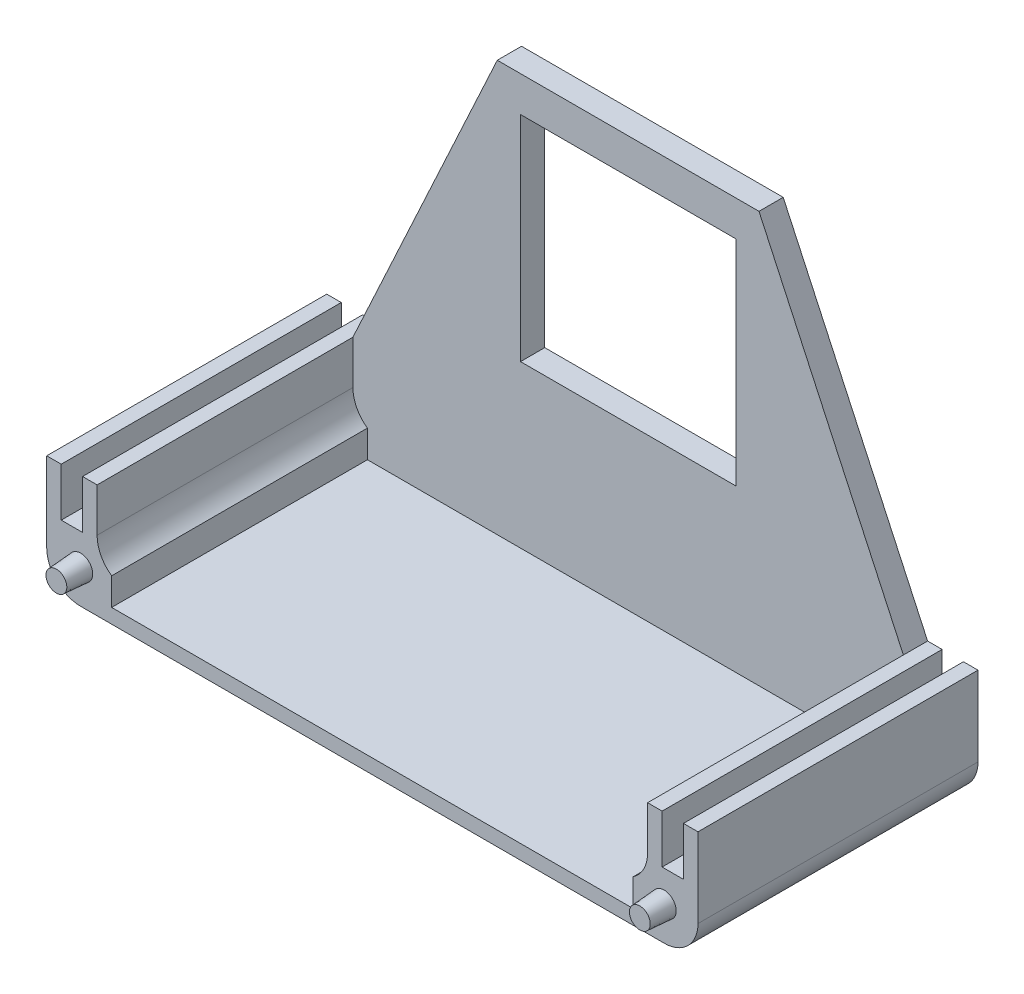
SolidWorks part; units mm, degrees
ref_plane "Спереди" through (0, 0, 0) normal (0, 0, 1) x (1, 0, 0)
ref_plane "Сверху" through (0, 0, 0) normal (0, 1, 0) x (1, 0, 0)
ref_plane "Справа" through (0, 0, 0) normal (1, 0, 0) x (0, 0, -1)
sketch "Sketch1" plane through (0, 0, 0) normal (0, 0, 1) x (1, 0, 0)
  line L21 (-42.2, 12.3095) -> (42.2, 12.3095) construction
  line L33 (-67.2, 104.5095) -> (-67.2, 19.3095) construction
  line L38 (67.2, 19.3095) -> (67.2, 104.5095) construction
  line L40 (56.8, 26.7095) -> (56.8, 97.1095) construction
  line L42 (53.8, 15.3095) -> (53.8, 20.965) construction
  line L43 (-56.8, 97.1095) -> (-56.8, 26.7095) construction
  line L44 (-53.8, 20.965) -> (-53.8, 15.3095) construction
  line L45 (-53.8, 15.3095) -> (53.8, 15.3095) construction
  line L46 (-60.2, 12.3095) -> (60.2, 12.3095)
  line L47 (-67.2, 35.7095) -> (-67.2, 19.3095)
  line L48 (67.2, 19.3095) -> (67.2, 35.7095)
  line L49 (56.8, 26.7095) -> (56.8, 35.7095)
  line L50 (53.8, 15.3095) -> (53.8, 20.965)
  line L51 (-56.8, 35.7095) -> (-56.8, 26.7095)
  line L52 (-53.8, 20.965) -> (-53.8, 15.3095)
  line L53 (-53.8, 15.3095) -> (53.8, 15.3095)
  line L54 (-59.8, 100.1095) -> (-59.8, 25.7095) construction
  line L55 (-59.8, 25.7095) -> (-64.2, 25.7095) construction
  line L56 (-64.2, 25.7095) -> (-64.2, 104.5095) construction
  line L57 (64.2, 104.5095) -> (64.2, 25.7095) construction
  line L58 (59.8, 25.7095) -> (59.8, 100.1095) construction
  line L59 (64.2, 25.7095) -> (59.8, 25.7095) construction
  line L60 (-59.8, 35.7095) -> (-59.8, 25.7095)
  line L61 (-59.8, 25.7095) -> (-64.2, 25.7095)
  line L62 (-64.2, 25.7095) -> (-64.2, 35.7095)
  line L63 (64.2, 35.7095) -> (64.2, 25.7095)
  line L64 (59.8, 25.7095) -> (59.8, 35.7095)
  line L65 (64.2, 25.7095) -> (59.8, 25.7095)
  line L66 (-56.8, 35.7095) -> (56.8, 35.7095) construction
  line L69 (-67.2, 35.7095) -> (-64.2, 35.7095)
  line L70 (-59.8, 35.7095) -> (-56.8, 35.7095)
  line L71 (56.8, 35.7095) -> (59.8, 35.7095)
  line L72 (64.2, 35.7095) -> (67.2, 35.7095)
  arc A8 (-67.2, 19.3095) -> (-60.2, 12.3095) centre (-60.2, 19.3095) ccw construction
  arc A9 (60.2, 12.3095) -> (67.2, 19.3095) centre (60.2, 19.3095) ccw construction
  arc A10 (53.8, 20.965) -> (56.8, 26.7095) centre (49.8, 26.7095) ccw construction
  arc A11 (-56.8, 26.7095) -> (-53.8, 20.965) centre (-49.8, 26.7095) ccw construction
  arc A12 (-67.2, 19.3095) -> (-60.2, 12.3095) centre (-60.2, 19.3095) ccw
  arc A13 (60.2, 12.3095) -> (67.2, 19.3095) centre (60.2, 19.3095) ccw
  arc A14 (53.8, 20.965) -> (56.8, 26.7095) centre (49.8, 26.7095) ccw
  arc A15 (-56.8, 26.7095) -> (-53.8, 20.965) centre (-49.8, 26.7095) ccw
  dimension "D1" = 10
extrude "Extrude2" add sketch "Sketch1" along normal up to vertex (57.786 mm away)
sketch "Sketch2" plane through (0, 0, 57.786) normal (0, 0, 1) x (1, 0, 0)
  circle A0 centre (-60.2, 19.3095) radius 2.5
  circle A1 centre (60.2, 19.3095) radius 2.5
  point P0 (-60.2, 19.3095)
  point P1 (60.2, 19.3095)
  dimension "D1" = 5
extrude "Extrude3" add sketch "Sketch2" along normal blind 5 draft 4
sketch "Sketch4" plane through (0, 0, 0) normal (0, 0, -1) x (-1, 0, 0)
  circle A0 centre (-60.2, 19.3095) radius 2.6
  circle A1 centre (60.2, 19.3095) radius 2.6
  dimension "D1" = 5.2
extrude "Cut-Extrude1" cut sketch "Sketch4" against normal blind 5.2 draft 3.8
sketch "Sketch3" plane through (0, 0, 0) normal (0, 0, -1) x (-1, 0, 0)
  line L0 (-27, 100.1095) -> (27, 100.1095)
  line L5 (-27, 100.1095) -> (-56.8, 35.7095)
  line L6 (27, 100.1095) -> (56.8, 35.7095)
  line L7 (-56.8, 35.7095) -> (-56.8, 26.7095) construction
  line L8 (-53.8, 20.965) -> (-53.8, 15.3095) construction
  line L11 (-53.8, 15.3095) -> (53.8, 15.3095) construction
  line L29 (53.8, 15.3095) -> (53.8, 20.965) construction
  line L30 (56.8, 26.7095) -> (56.8, 35.7095) construction
  line L31 (-56.8, 35.7095) -> (-56.8, 26.7095)
  line L32 (-53.8, 20.965) -> (-53.8, 15.3095)
  line L33 (-53.8, 15.3095) -> (53.8, 15.3095)
  line L34 (53.8, 15.3095) -> (53.8, 20.965)
  line L35 (56.8, 26.7095) -> (56.8, 35.7095)
  line L36 (-59.8, 100.1095) -> (59.8, 100.1095) construction
  line L37 (22.2091, 48.6403) -> (22.2091, 92.8045) construction
  line L38 (-22.2091, 92.8045) -> (22.2091, 92.8045) construction
  line L39 (-22.2091, 48.6403) -> (-22.2091, 92.8045) construction
  line L40 (-22.2091, 48.6403) -> (22.2091, 48.6403) construction
  line L41 (22.2091, 48.6403) -> (22.2091, 92.8045)
  line L42 (-22.2091, 92.8045) -> (22.2091, 92.8045)
  line L43 (-22.2091, 48.6403) -> (-22.2091, 92.8045)
  line L44 (-22.2091, 48.6403) -> (22.2091, 48.6403)
  arc A4 (-56.8, 26.7095) -> (-53.8, 20.965) centre (-49.8, 26.7095) ccw construction
  arc A5 (53.8, 20.965) -> (56.8, 26.7095) centre (49.8, 26.7095) ccw construction
  arc A6 (-56.8, 26.7095) -> (-53.8, 20.965) centre (-49.8, 26.7095) ccw
  arc A7 (53.8, 20.965) -> (56.8, 26.7095) centre (49.8, 26.7095) ccw
  point P6 (0, 100.1095)
  dimension "D1" = 54
extrude "Extrude4" add sketch "Sketch3" against normal blind 5 separate body
sketch "Sketch5" [suppressed] plane through (-60, 0, 0) normal (0, 0, 1) x (1, 0, 0)
  line L3 (107.5, 70.3095) -> (107.5, 30.3095) construction
  line L4 (112.5, 70.3095) -> (112.5, 30.3095)
  line L5 (102.5, 70.3095) -> (102.5, 30.3095)
  line L6 (12.5, 70.3095) -> (12.5, 30.3095) construction
  line L7 (17.5, 70.3095) -> (17.5, 30.3095)
  line L8 (7.5, 70.3095) -> (7.5, 30.3095)
  line L9 (107.5, 50.3095) -> (12.5, 50.3095) construction
  line L22 (113.8, 15.3095) -> (6.2, 15.3095) construction
  line L24 (119.8, 35.7095) -> (119.8, 100.1095)
  line L25 (119.8, 100.1095) -> (0.2, 100.1095)
  line L26 (0.2, 100.1095) -> (0.2, 35.7095)
  line L27 (119.8, 35.7095) -> (116.8, 35.7095) construction
  line L28 (116.8, 35.7095) -> (116.8, 26.7095) construction
  line L29 (113.8, 20.965) -> (113.8, 15.3095) construction
  line L30 (6.2, 15.3095) -> (6.2, 20.965) construction
  line L31 (3.2, 26.7095) -> (3.2, 35.7095) construction
  line L32 (3.2, 35.7095) -> (0.2, 35.7095) construction
  line L33 (119.8, 35.7095) -> (116.8, 35.7095)
  line L34 (116.8, 35.7095) -> (116.8, 26.7095)
  line L35 (113.8, 20.965) -> (113.8, 15.3095)
  line L36 (113.8, 15.3095) -> (6.2, 15.3095)
  line L37 (6.2, 15.3095) -> (6.2, 20.965)
  line L38 (3.2, 26.7095) -> (3.2, 35.7095)
  line L39 (3.2, 35.7095) -> (0.2, 35.7095)
  line L40 (0.4, 100.3095) -> (119.6, 100.3095) construction
  arc A0 (112.5, 70.3095) -> (102.5, 70.3095) centre (107.5, 70.3095) ccw
  arc A1 (102.5, 30.3095) -> (112.5, 30.3095) centre (107.5, 30.3095) ccw
  arc A7 (113.8, 20.965) -> (116.8, 26.7095) centre (109.8, 26.7095) ccw construction
  arc A8 (3.2, 26.7095) -> (6.2, 20.965) centre (10.2, 26.7095) ccw construction
  arc A9 (113.8, 20.965) -> (116.8, 26.7095) centre (109.8, 26.7095) ccw
  arc A10 (3.2, 26.7095) -> (6.2, 20.965) centre (10.2, 26.7095) ccw
  arc A11 (17.5, 70.3095) -> (7.5, 70.3095) centre (12.5, 70.3095) ccw
  arc A12 (7.5, 30.3095) -> (17.5, 30.3095) centre (12.5, 30.3095) ccw
  point P7 (60, 15.3095)
  point P11 (107.5, 50.3095)
  point P19 (12.5, 50.3095)
  point P31 (60, 50.3095)
  dimension "D5" = 10
  dimension "D1" = 0.2
  dimension "D2" = 95
  dimension "D3" = 40
  dimension "D4" = 15
extrude "Extrude5" [suppressed] add sketch "Sketch5" along normal up to vertex
sketch "Sketch6" [suppressed] plane through (0, 100.1095, 0) normal (0, 1, 0) x (1, 0, 0)
  circle A0 centre (-52.5, -12.5) radius 1.6 construction
  circle A1 centre (52.5, -12.5) radius 1.6 construction
  circle A2 centre (-52.5, -12.5) radius 1.6
  circle A3 centre (52.5, -12.5) radius 1.6
extrude "Cut-Extrude2" [suppressed] cut sketch "Sketch6" against normal blind 10
sketch "Sketch7" [suppressed] plane through (0, 100.1095, 0) normal (0, 1, 0) x (1, 0, 0)
  circle A0 centre (-52.5, -7.3) radius 1.6 construction
  circle A1 centre (52.5, -7.3) radius 1.6 construction
  circle A2 centre (-52.5, -7.3) radius 1.6
  circle A3 centre (52.5, -7.3) radius 1.6
extrude "Cut-Extrude3" [suppressed] cut sketch "Sketch7" against normal blind 10
sketch "Sketch8" [suppressed] plane through (0, 0, 0) normal (0, 0, -1) x (-1, 0, 0)
  line L0 (-36, 44.4095) -> (36, 44.4095) construction
  line L1 (-34, 44.4095) -> (34, 44.4095) construction
  circle A0 centre (-36, 44.4095) radius 1.9
  circle A1 centre (36, 44.4095) radius 1.9
  point P6 (-34, 44.4095)
  point P7 (34, 44.4095)
  point P12 (0, 44.4095)
  point P13 (0, 44.4095)
  dimension "D1" = 3.8
  dimension "D2" = 2
extrude "Cut-Extrude4" [suppressed] cut sketch "Sketch8" against normal through all
sketch "Sketch9" [suppressed] plane through (0, 12.3095, 0) normal (0, -1, 0) x (1, 0, 0)
  line L1 (0, 80) -> (-8.2649, 91.125) construction
  line L2 (-8.2649, 91.125) -> (-16.5297, 102.25) construction
  line L3 (-16.5297, 102.25) -> (-24.7946, 113.375) construction
  line L4 (-24.7946, 113.375) -> (-33.0595, 124.5) construction
  circle A1 centre (0, 80) radius 57.5 construction
  circle A2 centre (-8.2649, 91.125) radius 2.9259
  circle A3 centre (-16.5297, 102.25) radius 2.9259
  circle A5 centre (-24.7946, 113.375) radius 2.9259
  circle A6 centre (11.125, 88.2649) radius 2.9259
  circle A7 centre (8.2649, 68.875) radius 2.9259
  circle A8 centre (-11.125, 71.7351) radius 2.9259
  circle A10 centre (4.0448, 107.4214) radius 2.9259
  circle A11 centre (22.25, 96.5297) radius 2.9259
  circle A12 centre (27.4214, 75.9552) radius 2.9259
  circle A13 centre (16.5297, 57.75) radius 2.9259
  circle A14 centre (-4.0448, 52.5786) radius 2.9259
  circle A15 centre (-22.25, 63.4703) radius 2.9259
  circle A16 centre (-4.7853, 121.3009) radius 2.9259
  circle A17 centre (16.5063, 118.1603) radius 2.9259
  circle A18 centre (33.375, 104.7946) radius 2.9259
  circle A19 centre (41.3009, 84.7853) radius 2.9259
  circle A20 centre (38.1603, 63.4937) radius 2.9259
  circle A21 centre (24.7946, 46.625) radius 2.9259
  circle A22 centre (4.7853, 38.6991) radius 2.9259
  circle A23 centre (-16.5063, 41.8397) radius 2.9259
  circle A24 centre (-33.375, 55.2054) radius 2.9259
  circle A25 centre (-41.3009, 75.2147) radius 2.9259
  circle A26 centre (-27.4214, 84.0448) radius 2.9259
  circle A27 centre (-38.1603, 96.5063) radius 2.9259
  point P4 (0, 80)
  dimension "D1" = 115
  dimension "D2" = 4
  dimension "D3" = 8
  dimension "D4" = 12
extrude "Cut-Extrude5" [suppressed] cut sketch "Sketch9" against normal blind 10
equation "\"pin_l\"=5"
equation "\"D1@Extrude3\"=\"pin_l\""
equation "\"pin_skew\"=4"
equation "\"D3@Extrude3\"=\"pin_skew\""
equation "\"pin_r\"=5"
equation "\"D1@Sketch2\"=\"pin_r\""
equation "\"thickness\"=4"
equation "\"D1@Sketch4\"=\"pin_r\"+0.2"
equation "\"D1@Cut-Extrude1\"=\"pin_l\"+0.2"
equation "\"D3@Cut-Extrude1\"=\"pin_skew\"-0.2"
equation "\"M4_plastic_thread\"=3.8"
equation "\"D1@Sketch8\"=\"M4_plastic_thread\""
equation "\"M3_plastic_thread\" = 2.8"
